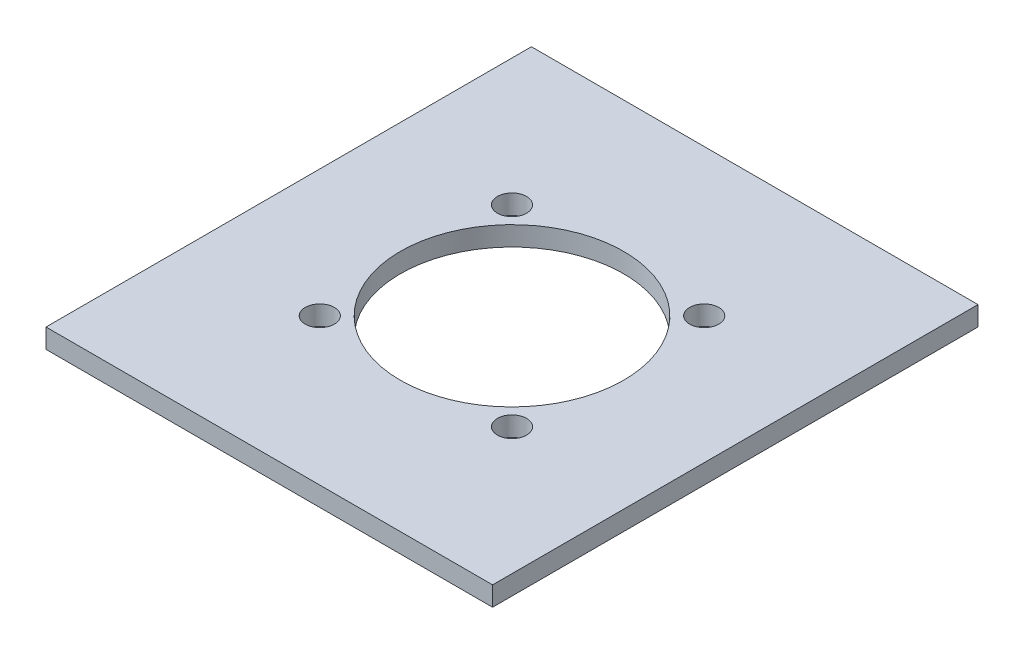
SolidWorks part; units mm, degrees
ref_plane "Front Plane" through (0, 0, 0) normal (0, 0, 1) x (1, 0, 0)
ref_plane "Top Plane" through (0, 0, 0) normal (0, 1, 0) x (1, 0, 0)
ref_plane "Right Plane" through (0, 0, 0) normal (1, 0, 0) x (0, 0, -1)
sketch "Sketch1" plane through (0, 0, 0) normal (0, 1, 0) x (1, 0, 0)
  line L1 (-23, -25) -> (23, -25)
  line L2 (-23, -25) -> (-23, 25)
  line L3 (-23, 25) -> (23, 25)
  line L4 (23, -25) -> (23, 25)
  line L5 (-23, -25) -> (23, 25) construction
  line L6 (-23, 25) -> (23, -25) construction
  point P0 (0, 0)
  dimension "D1" = 46
  dimension "D2" = 50
extrude "Boss-Extrude1" add sketch "Sketch1" along normal blind 2
sketch "Sketch2" plane through (0, 2, 0) normal (0, 1, 0) x (1, 0, 0)
  circle A0 centre (0, 0) radius 11.5
  dimension "D1" = 23
extrude "Cut-Extrude2" cut sketch "Sketch2" against normal through all contours A0
sketch "Sketch3" plane through (0, 2, 0) normal (0, 1, 0) x (1, 0, 0)
  line L0 (-9.8995, -9.8995) -> (9.8995, 9.8995) construction
  line L1 (-9.8995, 9.8995) -> (9.8995, -9.8995) construction
  line L2 (0, 5.0345) -> (0, -5.0345) construction
  circle A0 centre (0, 0) radius 14 construction
  circle A5 centre (9.8995, 9.8995) radius 1.5
  circle A6 centre (-9.8995, 9.8995) radius 1.5
  circle A7 centre (-9.8995, -9.8995) radius 1.5
  circle A8 centre (9.8995, -9.8995) radius 1.5
  point P14 (0, 0)
  point P17 (0, 0)
  point P20 (0, 0)
  dimension "D1" = 28
  dimension "D2" = 3
  dimension "D3" = 45
  dimension "D4" = 90
extrude "Cut-Extrude3" cut sketch "Sketch3" against normal through all
